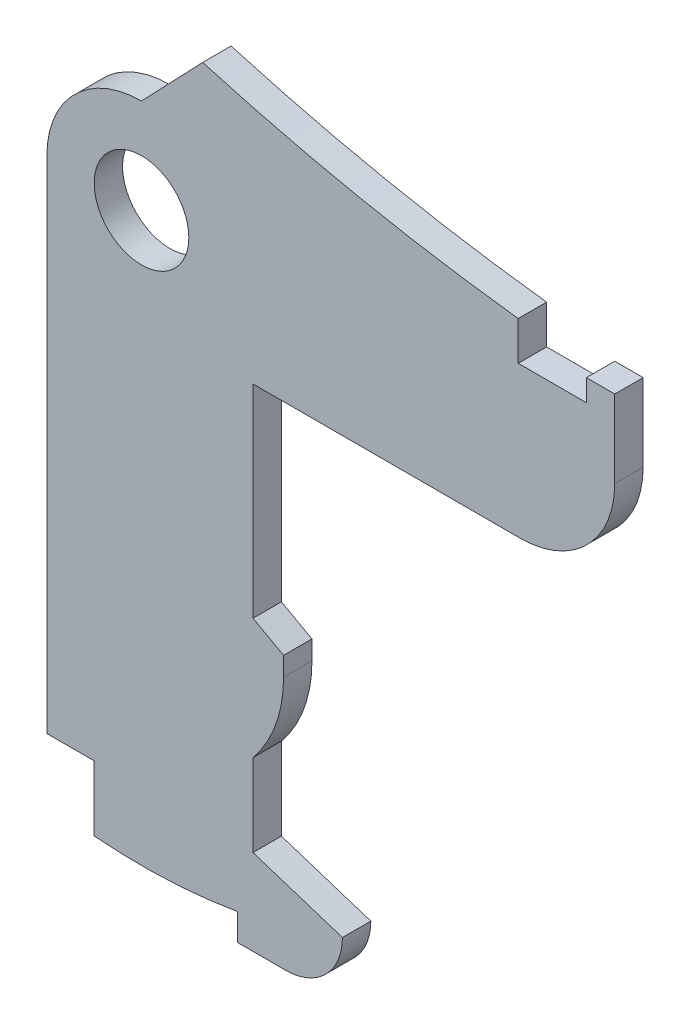
SolidWorks part; units mm, degrees
ref_plane "정면" through (0, 0, 0) normal (0, 0, 1) x (1, 0, 0)
ref_plane "윗면" through (0, 0, 0) normal (0, 1, 0) x (1, 0, 0)
ref_plane "우측면" through (0, 0, 0) normal (1, 0, 0) x (0, 0, -1)
sketch "스케치1" plane through (0, 0, 0) normal (0, 0, 1) x (1, 0, 0)
  line L0 (28.1634, -41.2491) -> (23.65, -39.725)
  line L1 (17.6552, -8.2873) -> (21.1871, -4.904)
  line L2 (53.4867, -33.1492) -> (56.7186, -29.7659)
  line L3 (59.3761, -60.24) -> (59.3761, -64.5868)
  line L4 (73.3867, -33.1492) -> (73.3867, -35.1985)
  line L5 (73.3867, -35.1985) -> (76.9867, -35.1985)
  line L6 (76.9867, -35.1985) -> (76.9867, -34.0533)
  line L7 (76.9867, -34.0533) -> (78.4867, -34.0533)
  line L8 (78.4867, -34.0533) -> (78.4867, -38.1492)
  line L9 (73.4867, -43.1492) -> (59.3761, -43.1492)
  line L10 (59.3761, -43.1492) -> (59.3761, -53.868)
  line L11 (58.5629, -69.1109) -> (61.1004, -69.1109)
  line L12 (48.4867, -64.5869) -> (48.4867, -38.1492)
  line L15 (37.5552, -8.5081) -> (37.5552, -10.3366)
  line L16 (37.5552, -10.3366) -> (41.1552, -10.3366)
  line L18 (50.9867, -68.0237) -> (50.9867, -64.5869)
  line L19 (50.9867, -64.5869) -> (48.4867, -64.5869)
  line L20 (41.1552, -10.3366) -> (41.1552, -9.1914)
  line L21 (41.1552, -9.1914) -> (42.6552, -9.1914)
  line L22 (42.6552, -9.1914) -> (42.6552, -13.2873)
  line L23 (37.6552, -18.2873) -> (23.65, -18.2873)
  line L24 (23.65, -18.2873) -> (23.65, -39.725)
  line L25 (22.7313, -44.2491) -> (25.1634, -44.2491)
  line L26 (12.6552, -39.725) -> (12.6552, -13.2873)
  line L27 (58.5629, -67.6952) -> (58.5629, -69.1109)
  line L28 (59.3761, -60.24) -> (59.3761, -64.5868)
  line L31 (59.3761, -60.24) -> (59.3761, -64.5868)
  line L32 (60.9929, -55.7531) -> (60.9929, -54.7553)
  line L33 (15.1552, -43.1618) -> (15.1552, -39.725)
  line L34 (15.1552, -39.725) -> (12.6552, -39.725)
  line L35 (22.7313, -42.8333) -> (22.7313, -44.2491)
  line L36 (60.9929, -54.7553) -> (59.3761, -53.868)
  line L40 (64.1004, -66.1109) -> (59.3761, -64.5868)
  arc A0 (37.3363, -8.2601) -> (37.5552, -8.5081) centre (37.3052, -8.5081) cw
  arc A1 (25.1634, -44.2491) -> (28.1634, -41.2491) centre (25.1634, -41.2491) ccw
  circle A2 centre (53.4867, -38.1492) radius 2.5
  circle A3 centre (17.6552, -13.2873) radius 2.5
  arc A4 (53.4867, -33.1492) -> (48.4867, -38.1492) centre (53.4867, -38.1492) ccw
  arc A5 (50.9867, -68.0237) -> (58.5629, -67.6952) centre (53.4867, -38.1492) ccw
  arc A6 (17.6552, -8.2873) -> (12.6552, -13.2873) centre (17.6552, -13.2873) ccw
  arc A7 (15.1552, -43.1618) -> (22.7313, -42.8333) centre (17.6552, -13.2873) ccw
  arc A9 (37.3363, -8.2601) -> (21.1871, -4.904) centre (50.2016, 94.181) cw
  arc A10 (42.6552, -13.2873) -> (37.6552, -18.2873) centre (37.6552, -13.2873) cw
  arc A11 (73.3867, -33.1492) -> (56.7186, -29.7659) centre (85.5208, 69.3811) cw
  arc A12 (78.4867, -38.1492) -> (73.4867, -43.1492) centre (73.4867, -38.1492) cw
  arc A13 (60.9929, -55.7531) -> (59.3761, -60.24) centre (53.9584, -55.7531) cw
  arc A14 (61.1004, -69.1109) -> (64.1004, -66.1109) centre (61.1004, -66.1109) ccw
  point P4 (37.5552, -8.2873)
  dimension "D1" = 3.6
  dimension "D2" = 1.5
  dimension "D3" = 103.2458
  dimension "D5" = 5
  dimension "D6" = 5
  dimension "D4" = 0.25
  dimension "D8" = 3
  dimension "D9" = 5
  dimension "D10" = 5
  dimension "D13" = 3
  dimension "D7" = 30
  dimension "D11" = 30
  dimension "D12" = 1.5
  dimension "D17" = 3.6
extrude "보스-돌출1" add sketch "스케치1" along normal blind 1.5 contours L11 A14 L40 L3 A13 L32 L36 L10 L9 A12 L8 L7 L6 L5 L4 A11 L2 A4 L12 L19 L18 A5 L27 A2
